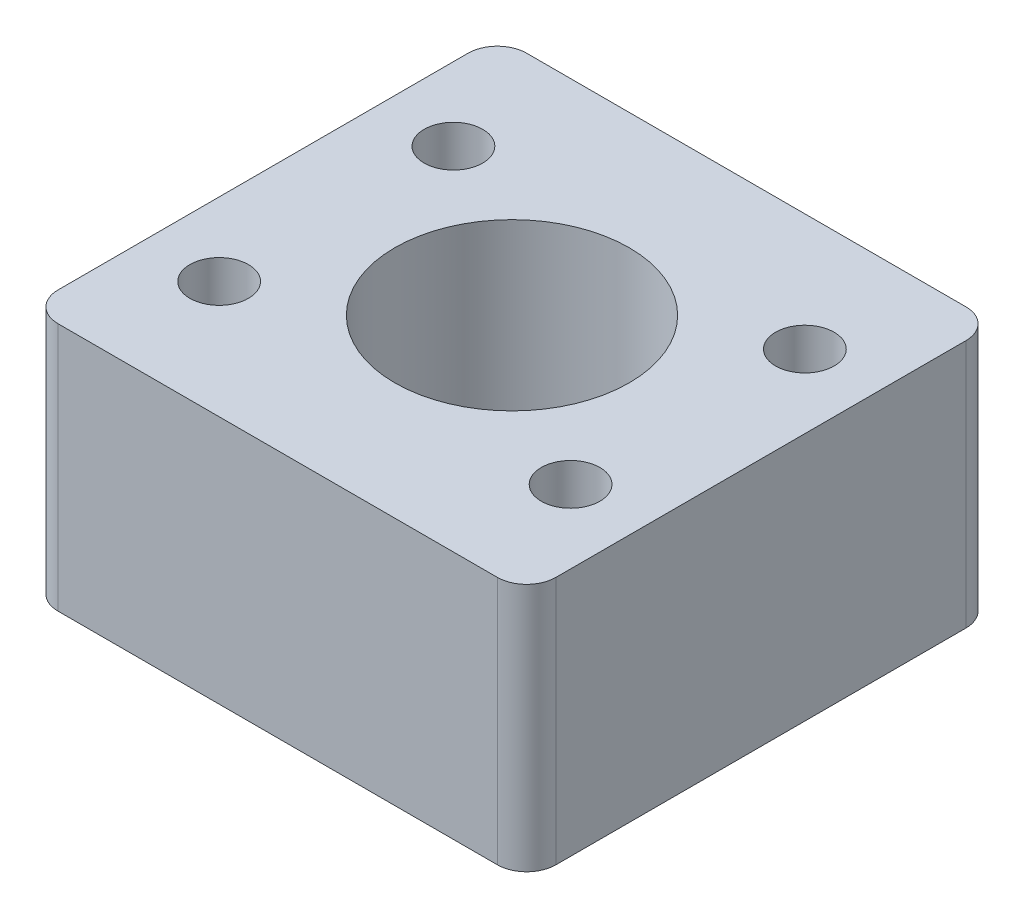
SolidWorks part; units mm, degrees
material "聚脂树脂"
ref_plane "前视基准面" through (0, 0, 0) normal (0, 0, 1) x (1, 0, 0)
ref_plane "上视基准面" through (0, 0, 0) normal (0, 1, 0) x (1, 0, 0)
ref_plane "右视基准面" through (0, 0, 0) normal (1, 0, 0) x (0, 0, -1)
other "Configuration Table"
sketch "草图1" plane through (0, 0, 0) normal (0, 1, 0) x (1, 0, 0)
  line L0 (0, 0) -> (0, 15.4433) construction
  line L1 (-8.5, -8) -> (8.5, -8)
  line L2 (-8.5, -8) -> (-8.5, 8)
  line L3 (-8.5, 8) -> (8.5, 8)
  line L4 (8.5, -8) -> (8.5, 8)
  line L5 (-8.5, -8) -> (8.5, 8) construction
  line L6 (-8.5, 8) -> (8.5, -8) construction
  line L7 (0, 0) -> (21.5354, 0) construction
  circle A0 centre (6, 4) radius 1
  circle A1 centre (-6, 4) radius 1
  circle A2 centre (6, -4) radius 1
  circle A3 centre (-6, -4) radius 1
  circle A4 centre (0, 0) radius 4
  point P0 (0, 0)
  dimension "D3" = 2
  dimension "D4" = 12
  dimension "D5" = 8
  dimension "D6" = 8
  dimension "D1" = 17
  dimension "D2" = 16
extrude "凸台-拉伸1" add sketch "草图1" along normal blind 8.5
fillet "圆角1" radius 1 4 edges at (8.5, 4.25, -8) (-8.5, 4.25, -8) (8.5, 4.25, 8) (-8.5, 4.25, 8)
